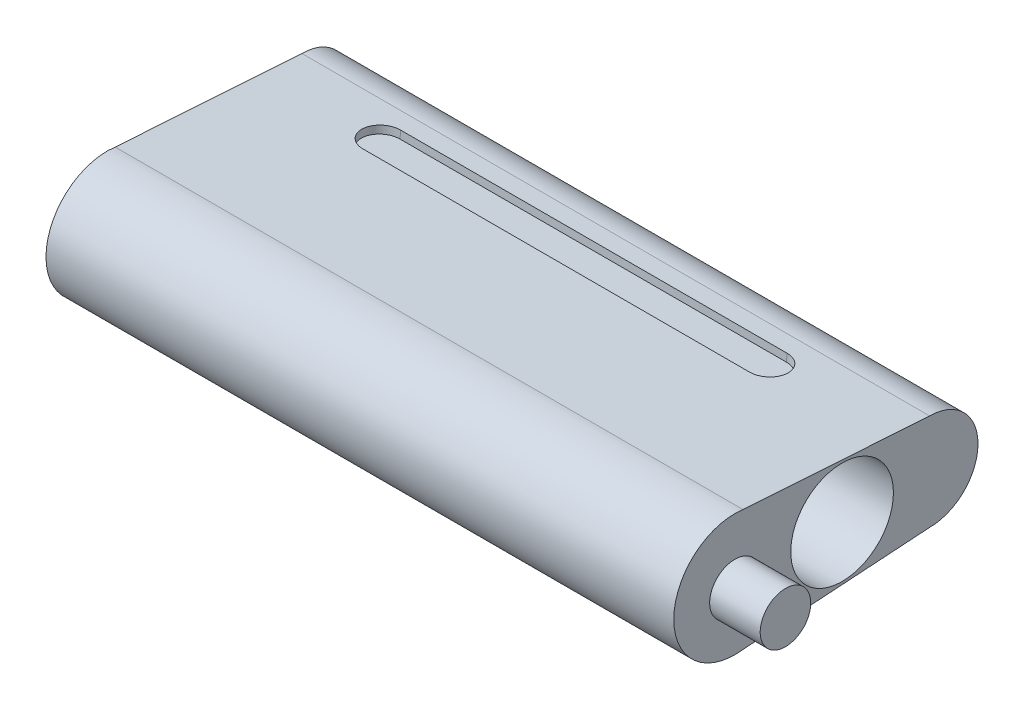
SolidWorks part; units mm, degrees
ref_plane "Front Plane" through (0, 0, 0) normal (0, 0, 1) x (1, 0, 0)
ref_plane "Top Plane" through (0, 0, 0) normal (0, 1, 0) x (1, 0, 0)
ref_plane "Right Plane" through (0, 0, 0) normal (1, 0, 0) x (0, 0, -1)
sketch "Sketch2" plane through (0, 0, 0) normal (1, 0, 0) x (0, 0, -1)
  line L0 (0, 1.2096) -> (0, -1.2643) construction
  line L3 (-1.2096, 0) -> (2.1576, 0) construction
  line L4 (2.1576, 0) -> (4.8087, 0) construction
  line L7 (3.8544, 0.9544) -> (3.8544, -0.9544) construction
  line L14 (0.1595, 1.1991) -> (3.8544, 0.9544)
  line L18 (0.1595, -1.1991) -> (3.8544, -0.9544)
  arc A0 (0.1595, 1.1991) -> (0.1595, -1.1991) centre (0, 0) ccw
  arc A2 (3.8544, -0.9544) -> (3.8544, 0.9544) centre (3.8544, 0) ccw
  dimension "D2" = 2.4192
  dimension "D3" = 1.9088
  dimension "D1" = 3.8544
extrude "Boss-Extrude1" add sketch "Sketch2" along normal blind 12.4192 contours L14 A2 L18 A0
sketch "Sketch3" plane through (12.4192, 0, 0) normal (1, 0, 0) x (0, 0, -1)
  circle A0 centre (2.1201, 0) radius 1.0156
  dimension "D1" = 2.0312
extrude "Cut-Extrude1" cut sketch "Sketch3" against normal blind 13.4192
sketch "Sketch4" plane through (12.4192, -0.0732, 0) normal (1, 0, 0) x (0, 0, -1)
  circle A0 centre (0, 0) radius 0.5
  point P2 (0.8711, -0.0995)
  point P3 (0.8897, -0.1735)
  point P4 (0.1408, 0)
  point P5 (0.2956, -0.0555)
  point P6 (0, 0)
  point P8 (0, 0)
  point P9 (0, 0)
  point P10 (0, 0)
  point P11 (0, 0)
  dimension "D1" = 1
sketch "Sketch6" plane through (12.4192, 0, 0) normal (1, 0, 0) x (0, 0, -1)
extrude "Boss-Extrude4" add sketch "Sketch4" along normal blind 1
sketch "Sketch7" plane through (0, 1.2043, -0.0797) normal (0, 0.9978, -0.0661) x (1, 0, 0)
  line L0 (2.3105, 3.4218) -> (9.9559, 3.4218)
  line L1 (2.3105, 2.6757) -> (9.9559, 2.6757)
  line L2 (0, 0.0799) -> (0, 3.7829) construction
  line L6 (12.4192, 0.0799) -> (0, 0.0799) construction
  arc A0 (2.3105, 3.4218) -> (2.3105, 2.6757) centre (2.3105, 3.0488) ccw
  arc A1 (9.9559, 2.6757) -> (9.9559, 3.4218) centre (9.9559, 3.0488) ccw
  point P18 (0, 0)
  dimension "D1" = 0.7461
  dimension "D2" = 7.6454
  dimension "D3" = 2.3105
  dimension "D6" = 2.5958
extrude "Cut-Extrude4" cut sketch "Sketch7" against normal blind 0.15
